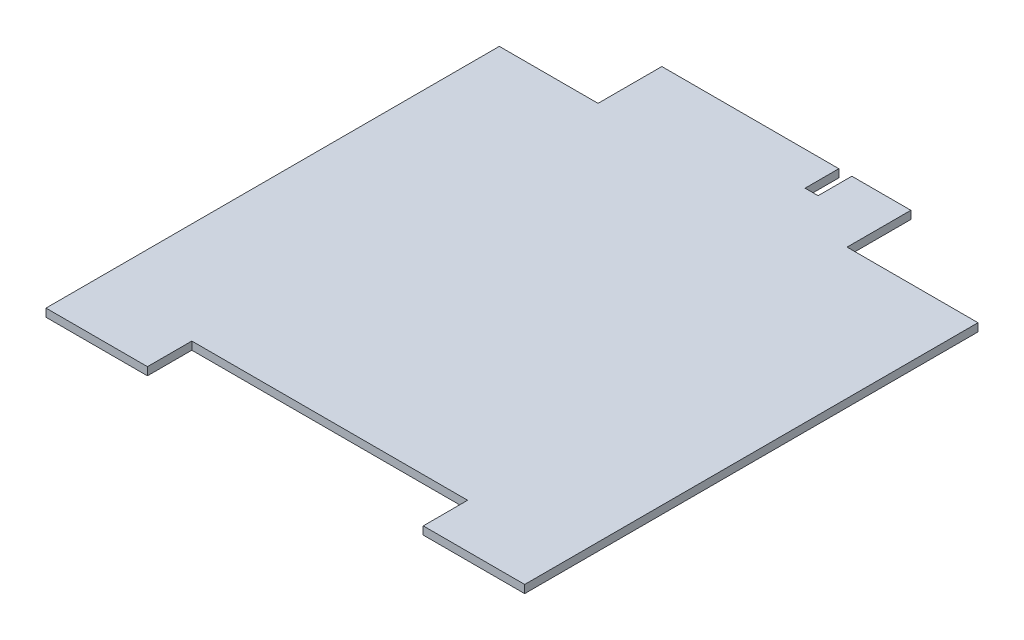
SolidWorks part; units mm, degrees
ref_plane "Front Plane" through (0, 0, 0) normal (0, 0, 1) x (1, 0, 0)
ref_plane "Top Plane" through (0, 0, 0) normal (0, 1, 0) x (1, 0, 0)
ref_plane "Right Plane" through (0, 0, 0) normal (1, 0, 0) x (0, 0, -1)
sketch "Sketch1" plane through (0, 0, 0) normal (0, 1, 0) x (1, 0, 0)
  line L1 (-47.9425, -45.4025) -> (47.9425, -45.4025)
  line L2 (-47.9425, -45.4025) -> (-47.9425, 45.4025)
  line L3 (-47.9425, 45.4025) -> (47.9425, 45.4025)
  line L4 (47.9425, -45.4025) -> (47.9425, 45.4025)
  line L5 (-47.9425, -45.4025) -> (47.9425, 45.4025) construction
  line L6 (-47.9425, 45.4025) -> (47.9425, -45.4025) construction
  line L7 (-28.1675, 45.4025) -> (21.7133, 45.4025)
  line L8 (-28.1675, 45.4025) -> (-28.1675, 58.1829)
  line L9 (-28.1675, 58.1829) -> (21.7133, 58.1829)
  line L10 (21.7133, 45.4025) -> (21.7133, 58.1829)
  point P0 (0, 0)
  dimension "D1" = 95.885
  dimension "D2" = 90.805
  dimension "D3" = 26.2292
  dimension "D4" = 12.7804
  dimension "D5" = 49.8808
extrude "Boss-Extrude1" add sketch "Sketch1" along normal blind 1.6 contours L3 L10 L9 L8 | L1 L4 L3 L2
sketch "Sketch2" plane through (0, 1.6, 0) normal (0, 1, 0) x (1, 0, 0)
  line L0 (-47.9425, -45.4025) -> (47.9425, -45.4025) construction
  line L1 (-27.6225, -45.4025) -> (27.6225, -45.4025)
  line L2 (-27.6225, -45.4025) -> (-27.6225, -36.5125)
  line L3 (-27.6225, -36.5125) -> (27.6225, -36.5125)
  line L4 (27.6225, -45.4025) -> (27.6225, -36.5125)
  line L5 (-28.1675, 58.1829) -> (21.7133, 58.1829) construction
  line L6 (7.2826, 58.1829) -> (9.8933, 58.1829)
  line L7 (7.2826, 58.1829) -> (7.2826, 51.4229)
  line L8 (7.2826, 51.4229) -> (9.8933, 51.4229)
  line L9 (9.8933, 58.1829) -> (9.8933, 51.4229)
  line L10 (-47.9425, -45.4025) -> (-47.9425, 45.4025) construction
  line L11 (21.7133, 45.4025) -> (21.7133, 58.1829) construction
  dimension "D1" = 8.89
  dimension "D2" = 20.32
  dimension "D3" = 55.245
  dimension "D4" = 6.76
  dimension "D5" = 2.6107
  dimension "D6" = 11.82
extrude "Cut-Extrude1" cut sketch "Sketch2" against normal up to surface (1.6 mm away) up to face at (-1.6136, 0, -25.8963)
